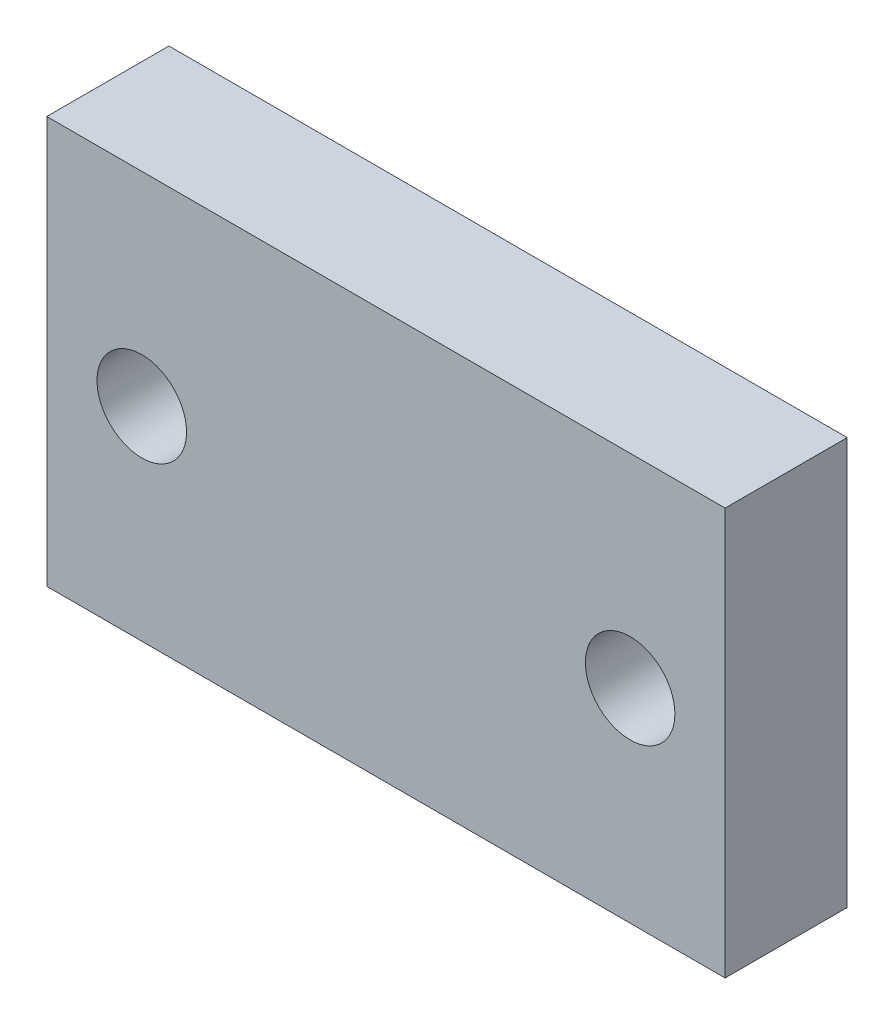
SolidWorks part; units mm, degrees
ref_plane "Front Plane" through (0, 0, 0) normal (0, 0, 1) x (1, 0, 0)
ref_plane "Top Plane" through (0, 0, 0) normal (0, 1, 0) x (1, 0, 0)
ref_plane "Right Plane" through (0, 0, 0) normal (1, 0, 0) x (0, 0, -1)
sketch "Sketch2" plane through (0, 0, 0) normal (0, 0, 1) x (1, 0, 0)
  line L1 (0, 0) -> (50, 0)
  line L2 (0, 0) -> (0, 30)
  line L3 (0, 30) -> (50, 30)
  line L4 (50, 0) -> (50, 30)
  dimension "D1" = 50
  dimension "D2" = 30
extrude "base" add sketch "Sketch2" along normal blind 9
hole_wizard "M6 Clearance Hole1" positions "Sketch3" profile "Sketch4" hole size "M6" standard "ANSI Metric" end condition through all
sketch "Sketch3" plane through (0, 0, 9) normal (0, 0, 1) x (1, 0, 0)
  line L0 (7, 15) -> (43, 15)
  line L2 (25, 15) -> (25, 30)
  line L3 (50, 30) -> (0, 30) construction
  line L5 (7, 15) -> (0, 15)
  line L6 (0, 30) -> (0, 0) construction
  point P0 (7, 15)
  point P2 (43, 15)
  dimension "D1" = 36
sketch "Sketch4" plane through (7, 15, 9) normal (1, 0, 0) x (0, -1, 0)
  line L0 (0, 0) -> (0, 9)
  line L1 (0, 9) -> (3.3, 9)
  line L2 (3.3, 9) -> (3.3, 0)
  line L5 (3.3, 0) -> (0, 0)
  line L11 (0, -6.35) -> (0, 107.95) construction
  dimension "Thru Hole Dia." = 6.6
  dimension "Thru Hole Depth" = 9
